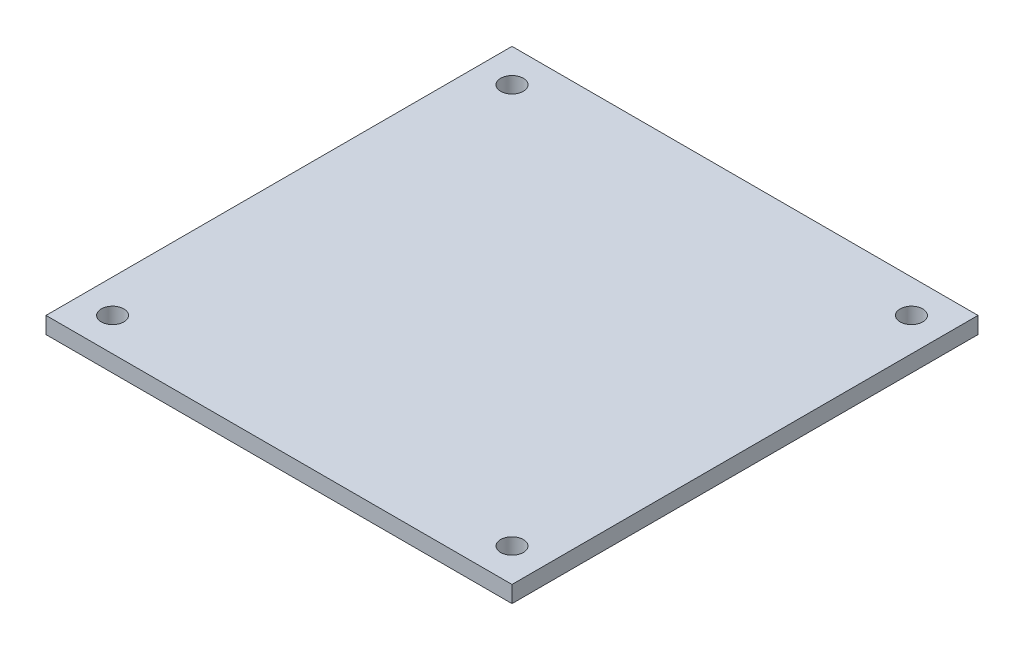
SolidWorks part; units mm, degrees
ref_plane "Front Plane" through (0, 0, 0) normal (0, 0, 1) x (1, 0, 0)
ref_plane "Top Plane" through (0, 0, 0) normal (0, 1, 0) x (1, 0, 0)
ref_plane "Right Plane" through (0, 0, 0) normal (1, 0, 0) x (0, 0, -1)
sketch "Sketch1" plane through (0, 0, 0) normal (0, 1, 0) x (1, 0, 0)
  line L0 (35, 70) -> (35, 0) construction
  line L1 (0, 0) -> (70, 0)
  line L2 (0, 0) -> (0, 70)
  line L3 (0, 70) -> (70, 70)
  line L4 (70, 0) -> (70, 70)
  line L5 (0, 35) -> (70, 35) construction
  circle A0 centre (65, 65) radius 1.7
  circle A2 centre (5, 65) radius 1.7
  circle A3 centre (65, 5) radius 1.7
  circle A4 centre (5, 5) radius 1.7
  dimension "D5" = 3.4
  dimension "D1" = 70
  dimension "D2" = 70
  dimension "D3" = 5
  dimension "D4" = 5
extrude "Plate" add sketch "Sketch1" along normal blind 2.5
equation "\"WallSep\"= ( 70mm - 60 ) / 2"
equation "\"D4@Sketch1\"=\"WallSep\""
equation "\"D3@Sketch1\"=\"WallSep\""
